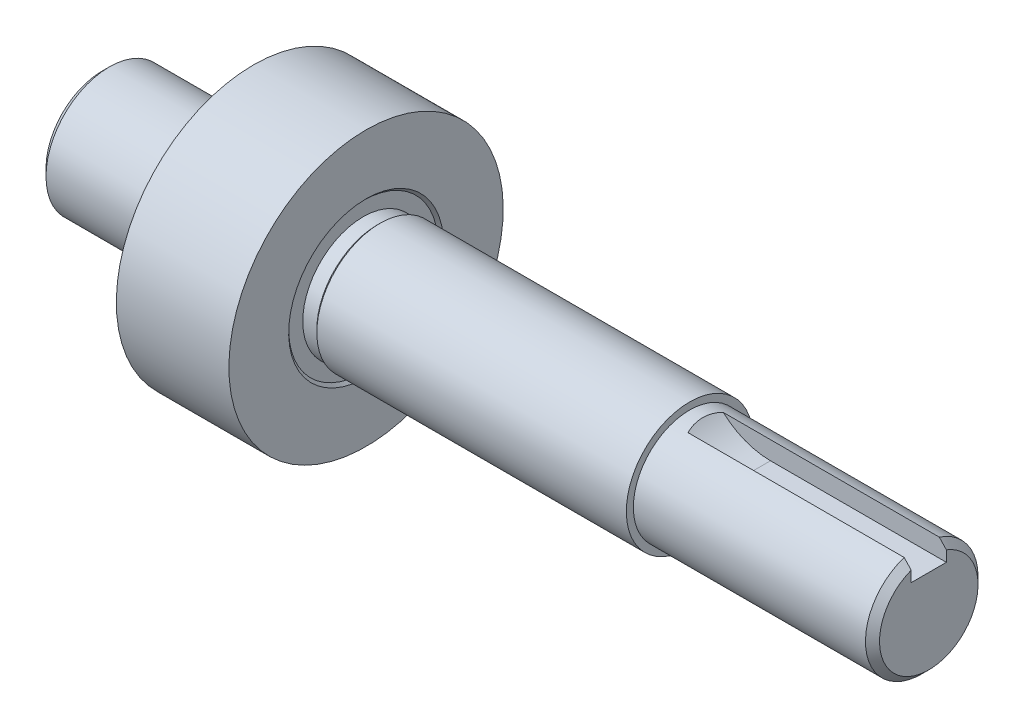
SolidWorks part; units mm, degrees
ref_plane "前视基准面" through (0, 0, 0) normal (0, 0, 1) x (1, 0, 0)
ref_plane "上视基准面" through (0, 0, 0) normal (0, 1, 0) x (1, 0, 0)
ref_plane "右视基准面" through (0, 0, 0) normal (1, 0, 0) x (0, 0, -1)
sketch "草图1" plane through (0, 0, 0) normal (0, 0, 1) x (1, 0, 0)
  line L0 (58.75, 0) -> (-58.75, 0) construction
  line L1 (-58.75, 0) -> (-58.75, 9)
  line L2 (-58.75, 9) -> (-39.25, 9)
  line L4 (-38.85, 8.6) -> (-36.85, 8.6)
  line L5 (-37.25, 11) -> (-37.25, 19.5)
  line L6 (-37.25, 19.5) -> (-21.25, 19.5)
  line L7 (-21.25, 19.5) -> (-21.25, 11)
  line L10 (-19.25, 9) -> (24.75, 9)
  line L11 (24.75, 9) -> (24.75, 8)
  line L12 (24.75, 8) -> (58.75, 8)
  line L13 (58.75, 8) -> (58.75, 0)
  line L15 (-39.25, 9) -> (-38.85, 8.6)
  line L16 (-36.85, 10.6) -> (-37.25, 11)
  line L17 (-36.85, 10.6) -> (-36.85, 8.6)
  line L18 (-19.25, 9) -> (-19.65, 8.6)
  line L19 (-19.65, 8.6) -> (-21.65, 8.6)
  line L20 (-21.65, 8.6) -> (-21.65, 10.6)
  line L21 (-21.65, 10.6) -> (-21.25, 11)
  line L22 (-58.75, 0) -> (58.75, 0)
  point P10 (-7.8924, 5.0116)
  point P11 (0, 0)
  point P12 (-6.8694, 7.9078)
  point P23 (0, 0)
  point P24 (-8.4315, 10.759)
  point P25 (-9.5194, 10.6)
  point P26 (-15.3357, 10.6)
  point P27 (-37.5067, 9)
  point P28 (0, 0)
  point P29 (0, 0)
  point P30 (0, 0)
  dimension "D2" = 117.5
  dimension "D3" = 34
  dimension "D4" = 16
  dimension "D5" = 21.5
  dimension "D6" = 16
  dimension "D7" = 18
  dimension "D8" = 39
  dimension "D9" = 0.4
  dimension "D10" = 0.4
  dimension "D11" = 2
  dimension "D12" = 45
  dimension "D13" = 45
  dimension "D14" = 2.4
  dimension "D15" = 0.4
  dimension "D16" = 0.4
  dimension "D17" = 45
  dimension "D18" = 45
  dimension "D19" = 2
  dimension "D20" = 18
revolve "旋转1" add sketch "草图1" angle 360 about L0
chamfer "倒角1" distance 1 angle 45 1 edges at (-58.75, 9, 0)
sketch "草图3" plane through (0, 0, 0) normal (0, 0, 1) x (1, 0, 0)
  line L0 (58.75, 5) -> (33.75, 5)
  line L1 (58.75, -8) -> (58.75, 8) construction
  line L2 (58.75, 8) -> (24.75, 8) construction
  line L3 (58.75, 5) -> (58.75, -8) construction
  line L4 (26.6086, 8) -> (26.6086, 13)
  line L5 (26.6086, 13) -> (58.75, 13)
  line L6 (58.75, 13) -> (58.75, 5)
  arc A0 (33.75, 5) -> (26.6086, 8) centre (33.75, 15) cw
  dimension "D1" = 10
  dimension "D2" = 25
  dimension "D3" = 13
  dimension "D4" = 8
extrude "切除-拉伸1" cut sketch "草图3" against normal mid plane 5
chamfer "倒角2" distance 1 angle 45 1 edges at (58.75, -8, 0)
